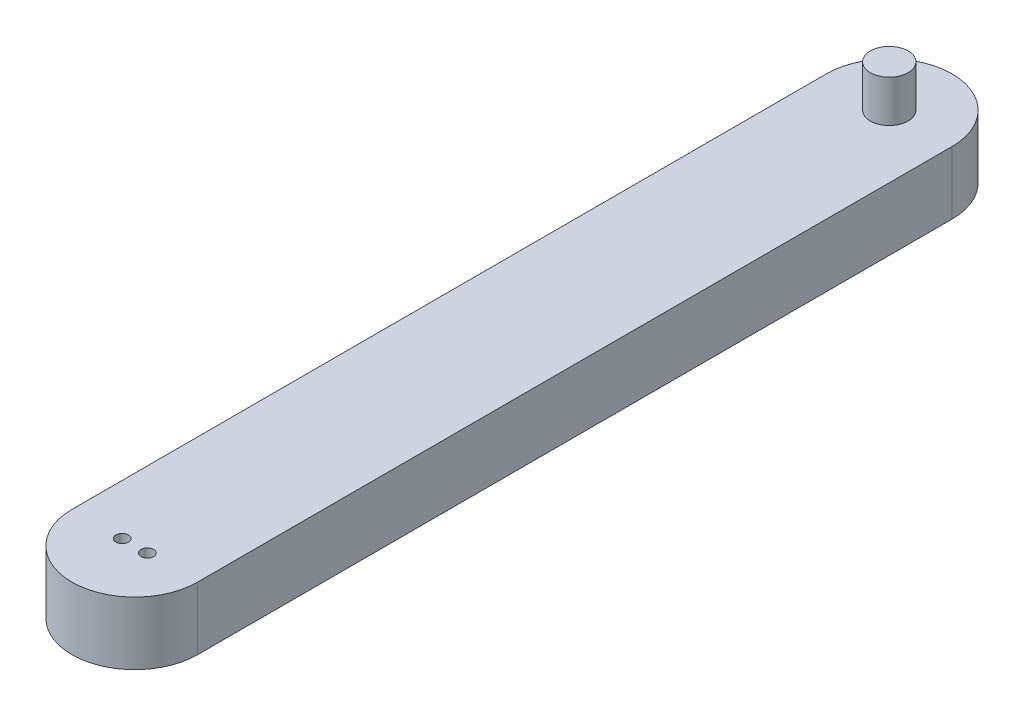
SolidWorks part; units mm, degrees
ref_plane "Front Plane" through (0, 0, 0) normal (0, 0, 1) x (1, 0, 0)
ref_plane "Top Plane" through (0, 0, 0) normal (0, 1, 0) x (1, 0, 0)
ref_plane "Right Plane" through (0, 0, 0) normal (1, 0, 0) x (0, 0, -1)
sketch "Sketch2" plane through (0, 0, 0) normal (0, 1, 0) x (1, 0, 0)
  line L0 (13.7545, 4.9188) -> (-1.2455, 4.9188) construction
  line L2 (-1.2455, 94.9188) -> (-1.2455, 4.9188)
  line L4 (13.7545, 94.9188) -> (13.7545, 4.9188)
  arc A0 (13.7545, 94.9188) -> (-1.2455, 94.9188) centre (6.2545, 94.9188) ccw
  arc A2 (-1.2455, 4.9188) -> (13.7545, 4.9188) centre (6.2545, 4.9188) ccw
  circle A3 centre (6.2545, 4.9188) radius 1.5 construction
  circle A4 centre (6.2545, 94.9188) radius 2.5 construction
  circle A5 centre (4.7545, 4.9188) radius 0.75
  circle A6 centre (7.7545, 4.9188) radius 0.75
  dimension "D3" = 5
  dimension "D4" = 3
  dimension "D5" = 1.5
  dimension "D6" = 1.5
  dimension "D1" = 90
  dimension "D2" = 15
extrude "Boss-Extrude1" add sketch "Sketch2" along normal blind 7.5 contours L2 A2 L4 A0
sketch "Sketch3" plane through (0, 0, 0) normal (0, -1, 0) x (1, 0, 0)
  line L0 (6.2545, -4.9188) -> (6.2545, -44.9188) construction
  line L1 (11.2545, -4.9188) -> (11.2545, -44.9188)
  line L2 (1.2545, -4.9188) -> (1.2545, -44.9188)
  arc A0 (11.2545, -4.9188) -> (1.2545, -4.9188) centre (6.2545, -4.9188) ccw
  arc A1 (1.2545, -44.9188) -> (11.2545, -44.9188) centre (6.2545, -44.9188) ccw
  point P3 (6.2545, -24.9188)
  dimension "D2" = 5
  dimension "D1" = 40
extrude "Cut-Extrude1" cut sketch "Sketch3" against normal blind 5 contours L1 A1 L2 A0
sketch "Sketch4" plane through (0, 7.5, 0) normal (0, 1, 0) x (1, 0, 0)
  circle A0 centre (6.2545, 94.9188) radius 2.25
  dimension "D1" = 4.5
extrude "Boss-Extrude2" add sketch "Sketch4" along normal blind 5 contours A0
